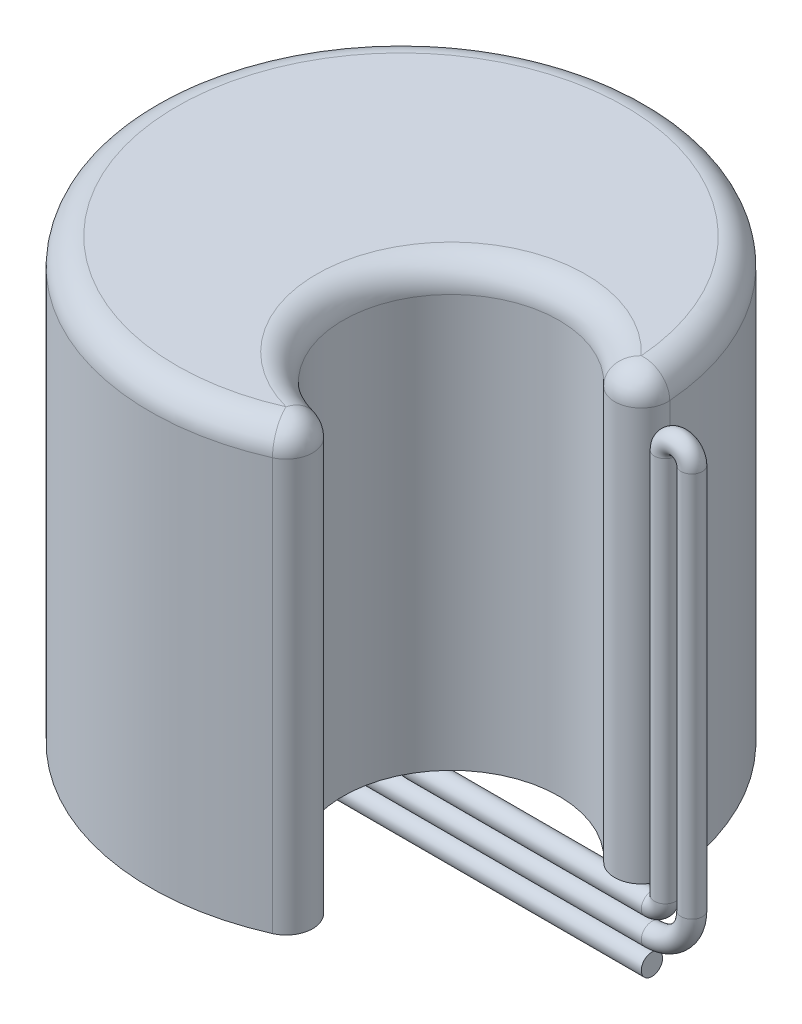
SolidWorks part; units mm, degrees
ref_plane "Front Plane" through (0, 0, 0) normal (0, 0, 1) x (1, 0, 0)
ref_plane "Top Plane" through (0, 0, 0) normal (0, 1, 0) x (1, 0, 0)
ref_plane "Right Plane" through (0, 0, 0) normal (1, 0, 0) x (0, 0, -1)
sketch "Sketch1" plane through (0, 0, 0) normal (0, 0, 1) x (1, 0, 0)
  line L0 (0, 0) -> (0, 96.4588) construction
  line L1 (0, 0) -> (59.9281, 0)
  line L2 (59.9281, 0) -> (59.9281, 104.775)
  line L3 (59.9281, 104.775) -> (0, 104.775)
  line L4 (0, 104.775) -> (0, 0)
  dimension "D1" = 119.8563
  dimension "D2" = 104.775
revolve "Revolve1" add sketch "Sketch1" angle 360 about L0
sketch "Sketch2" [suppressed] plane through (0, 0, 0) normal (0, 0, 1) x (1, 0, 0)
  line L0 (59.9281, 0) -> (59.9281, 25.4)
  line L1 (59.9281, 0) -> (59.9281, 104.775) construction
  line L2 (6.3406, -90.168) -> (4.7625, -90.168)
  line L3 (0, -92.0023) -> (0, 0) construction
  line L4 (6.3406, -90.168) -> (6.3406, -75.6009) construction
  line L5 (58.3406, 0) -> (58.3406, 25.4)
  line L6 (4.7625, -90.168) -> (4.7625, -88.972)
  line L8 (58.3406, 25.4) -> (59.9281, 25.4)
  line L9 (4.7625, -88.972) -> (-0.4412, -90.4774) construction
  line L10 (6.3406, -90.168) -> (0, -92.0023) construction
  arc A0 (59.9281, 0) -> (45.2901, -24.6305) centre (31.8871, 0) cw
  arc A1 (45.2901, -24.6305) -> (6.3406, -90.168) centre (80.9531, -90.168) ccw
  arc A2 (58.3406, 0) -> (44.5313, -23.2361) centre (31.8871, 0) cw
  arc A3 (44.5313, -23.2361) -> (4.7625, -88.972) centre (80.9531, -90.168) ccw
  dimension "D1" = 9.525
  dimension "D3" = 25.4
  dimension "D2" = 1.5875
revolve "Revolve5" [suppressed] add sketch "Sketch2" angle 19 about L3
pattern_circular "CirPattern2" [suppressed] count 12 over 360
sketch "Sketch5" [suppressed] plane through (0, 0, 0) normal (0, 0, 1) x (1, 0, 0)
  line L0 (0, 80.7892) -> (0, 111.125) construction
  line L1 (0, 104.775) -> (0, 0) construction
  line L2 (6.35, 111.125) -> (6.35, 104.775)
  line L3 (59.9281, 104.775) -> (-59.9281, 104.775) construction
  line L4 (0, 111.125) -> (0, 117.475) construction
  line L5 (-6.35, 111.125) -> (-6.35, 104.775)
  arc A0 (6.35, 111.125) -> (0, 117.475) centre (0, 111.125) ccw
  arc A1 (0, 117.475) -> (-6.35, 111.125) centre (0, 111.125) ccw
  dimension "D1" = 6.35
  dimension "D2" = 12.7
sketch "Sketch6" [suppressed] plane through (0, 104.775, 0) normal (0, 1, 0) x (1, 0, 0)
  line L0 (0, 0) -> (6.35, 0) construction
  circle A0 centre (6.35, 0) radius 2.54
  dimension "D1" = 5.08
sweep "Sweep1" [suppressed] add profiles "Sketch6" path "Sketch5"
ref_plane "Plane1" [suppressed] through (0, -115.568, 0) normal (0, -1, 0) x (-1, 0, 0)
sketch "Sketch15" [suppressed] plane through (0, 0, 0) normal (0, 0, 1) x (1, 0, 0)
  line L0 (0, 0) -> (0, -115.568) construction
  line L1 (6.3406, -90.168) -> (6.3406, -90.9618)
  line L2 (0, -115.568) -> (-8.2827, -115.568) construction
  line L3 (4.7531, -90.168) -> (4.7531, -90.9618)
  line L4 (4.7531, -90.168) -> (6.3406, -90.168)
  line L5 (-4.7531, -90.168) -> (-6.3406, -90.168)
  line L6 (-6.3406, -90.168) -> (-6.3406, -90.9618)
  line L7 (-4.7531, -90.168) -> (-4.7531, -90.9618)
  arc A0 (6.3406, -90.9618) -> (8.6816, -97.7536) centre (17.3633, -90.9618) ccw
  arc A1 (8.6816, -97.7536) -> (0, -115.568) centre (0, -104.5454) cw
  arc A2 (4.7531, -90.9618) -> (7.4313, -98.7317) centre (17.3633, -90.9618) ccw
  arc A3 (7.4313, -98.7317) -> (0, -113.9805) centre (0, -104.5454) cw
  arc A4 (-6.3406, -90.9618) -> (-8.6816, -97.7536) centre (-17.3633, -90.9618) cw
  arc A5 (-4.7531, -90.9618) -> (-7.4313, -98.7317) centre (-17.3633, -90.9618) cw
  arc A6 (-7.4313, -98.7317) -> (0, -113.9805) centre (0, -104.5454) ccw
  arc A7 (-8.6816, -97.7536) -> (0, -115.568) centre (0, -104.5454) ccw
  dimension "D2" = 1.5875
  dimension "D1" = 25.4
  dimension "D3" = 0.7937
extrude "Boss-Extrude2" [suppressed] add sketch "Sketch15" along normal mid plane 12.7
sketch "Sketch12" plane through (0, 0, 0) normal (0, 0, 1) x (1, 0, 0)
  line L0 (0, 0) -> (0, 19.2941) construction
  line L1 (0, 104.775) -> (0, 0) construction
  line L2 (3.175, -3.175) -> (59.9281, -3.175)
  line L3 (63.1031, 0) -> (63.1031, 92.075)
  line L4 (69.4531, 92.075) -> (69.4531, 0)
  line L5 (59.9281, -9.525) -> (-56.7531, -9.525)
  line L6 (-56.7531, -15.875) -> (59.9281, -15.875)
  line L7 (-59.9281, 0) -> (59.9281, 0) construction
  line L8 (-59.9281, 104.775) -> (-59.9281, 0) construction
  line L9 (59.9281, 0) -> (59.9281, 104.775) construction
  line L12 (59.9281, 104.775) -> (-59.9281, 104.775) construction
  arc A0 (0, 0) -> (3.175, -3.175) centre (3.175, 0) ccw
  arc A1 (59.9281, -3.175) -> (63.1031, 0) centre (59.9281, 0) ccw
  arc A2 (63.1031, 92.075) -> (69.4531, 92.075) centre (66.2781, 92.075) cw
  arc A3 (69.4531, 0) -> (59.9281, -9.525) centre (59.9281, 0) cw
  arc A4 (-56.7531, -9.525) -> (-56.7531, -15.875) centre (-56.7531, -12.7) ccw
  dimension "D1" = 3.175
  dimension "D2" = 12.7
sketch "Sketch13" plane through (0, 0, 0) normal (0, -1, 0) x (1, 0, 0)
  circle A0 centre (0, 0) radius 2.54
  dimension "D1" = 5.08
sweep "Sweep2" add profiles "Sketch13" path "Sketch12"
sketch "Sketch14" plane through (0, 104.775, 0) normal (0, 1, 0) x (1, 0, 0)
  line L0 (0, 0) -> (29.9366, -17.9877) construction
  line L1 (0, 0) -> (32.8444, 0) construction
  arc A0 (48.791, -0.3812) -> (23.2426, -42.9009) centre (29.9366, -17.9877) ccw
  circle A1 centre (0, 0) radius 59.9281 construction
  arc A2 (24.1542, -54.8448) -> (59.7648, 4.4211) centre (0, 0) ccw
  arc A3 (48.791, -0.3812) -> (59.7648, 4.4211) centre (53.4321, 3.9527) ccw
  arc A4 (23.2426, -42.9009) -> (24.1542, -54.8448) centre (21.5949, -49.0334) cw
  dimension "D1" = 51.5938
  dimension "D2" = 34.925
  dimension "D4" = 6.35
  dimension "D3" = 31
extrude "Cut-Extrude2" cut sketch "Sketch14" against normal blind 104.775
fillet "Fillet1" radius 6.35 4 edges at (27.9264, 104.775, 48.5502) (7.8243, 104.775, 4.7013) (55.9779, 104.775, 1.8647) (-51.3684, 104.775, -30.8653)
